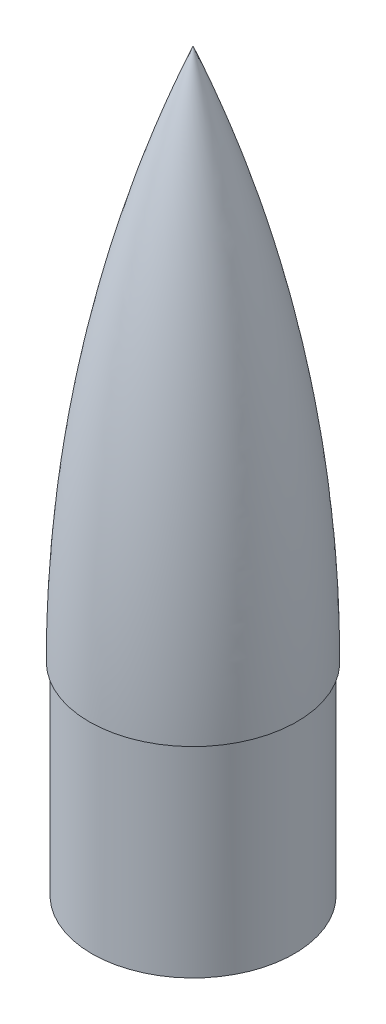
SolidWorks part; units mm, degrees
other "Markup1"
sketch "Sketch4" plane through (78.16, -154.2442, 78.16) normal (0.9651, -0.1718, 0.1975) x (-0.1686, -0.9851, -0.0334)
material "Thornel Mat VMA"
ref_plane "Front Plane" through (0, 0, 0) normal (0, 0, 1) x (1, 0, 0)
ref_plane "Top Plane" through (0, 0, 0) normal (0, 1, 0) x (1, 0, 0)
ref_plane "Right Plane" through (0, 0, 0) normal (1, 0, 0) x (0, 0, -1)
sketch "Sketch1" plane through (0, 0, 0) normal (0, 0, 1) x (1, 0, 0)
  line L3 (0, 0) -> (0, 398.8705) construction
  line L6 (0, 400) -> (0, 401.8534)
  line L8 (78.2, 0) -> (76.2, 0)
  line L9 (0, 400) -> (0, 396.4892)
  line L10 (76.2, 0) -> (-993.4203, 0) construction
  line L11 (0, 411.0234) -> (0, 614.1078) construction
  arc A0 (76.2, 0) -> (0, 396.4892) centre (-993.4203, 0) ccw
  arc A1 (78.2, 0) -> (0, 401.8534) centre (-993.4203, 0) ccw
  circle A2 centre (-993.4203, 0) radius 1069.6203 construction
  circle A3 centre (-993.4203, 0) radius 1071.6203 construction
  point P11 (0, 400)
  dimension "D1" = 400
  dimension "D2" = 3.5108
  dimension "D3" = 2
  dimension "D4" = 76.2
revolve "Revolve3" add sketch "Sketch1" angle 360 about L6
sketch "Sketch2" plane through (0, 0, 0) normal (0, 1, 0) x (1, 0, 0)
  circle A3 centre (0, 0) radius 76.2 construction
  circle A4 centre (0, 0) radius 76.2
  circle A5 centre (0, 0) radius 74.2
  dimension "D1" = 2
extrude "Boss-Extrude1" add sketch "Sketch2" against normal blind 152.4 and the other way blind 10
ref_plane "Plane2" through (0, 400, 0) normal (0, -1, 0) x (-1, 0, 0)
ref_plane "Plane4" through (0, 370, 0) normal (0, -1, 0) x (-1, 0, 0)
ref_plane "Plane3" through (0, -6.4, 0) normal (0, -1, 0) x (-1, 0, 0)
